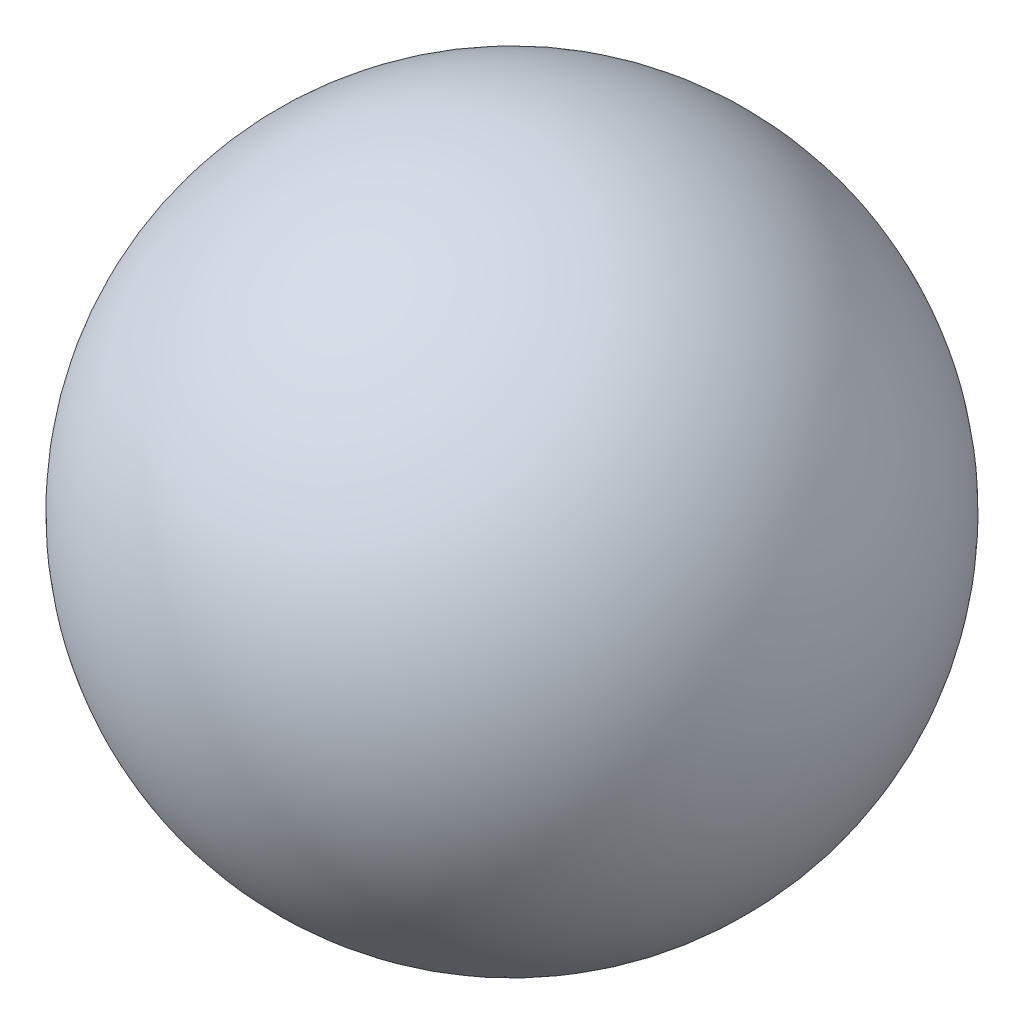
SolidWorks part; units mm, degrees
ref_plane "Front Plane" through (0, 0, 0) normal (0, 0, 1) x (1, 0, 0)
ref_plane "Top Plane" through (0, 0, 0) normal (0, 1, 0) x (1, 0, 0)
ref_plane "Right Plane" through (0, 0, 0) normal (1, 0, 0) x (0, 0, -1)
sketch "Sketch1" plane through (0, 0, 0) normal (0, 1, 0) x (1, 0, 0)
  line L0 (0, 88.9) -> (0, -88.9)
  arc A0 (0, 88.9) -> (0, -88.9) centre (0, 0) ccw
  point P6 (0, 0)
revolve "Revolve1" add sketch "Sketch1" angle 360 about L0
